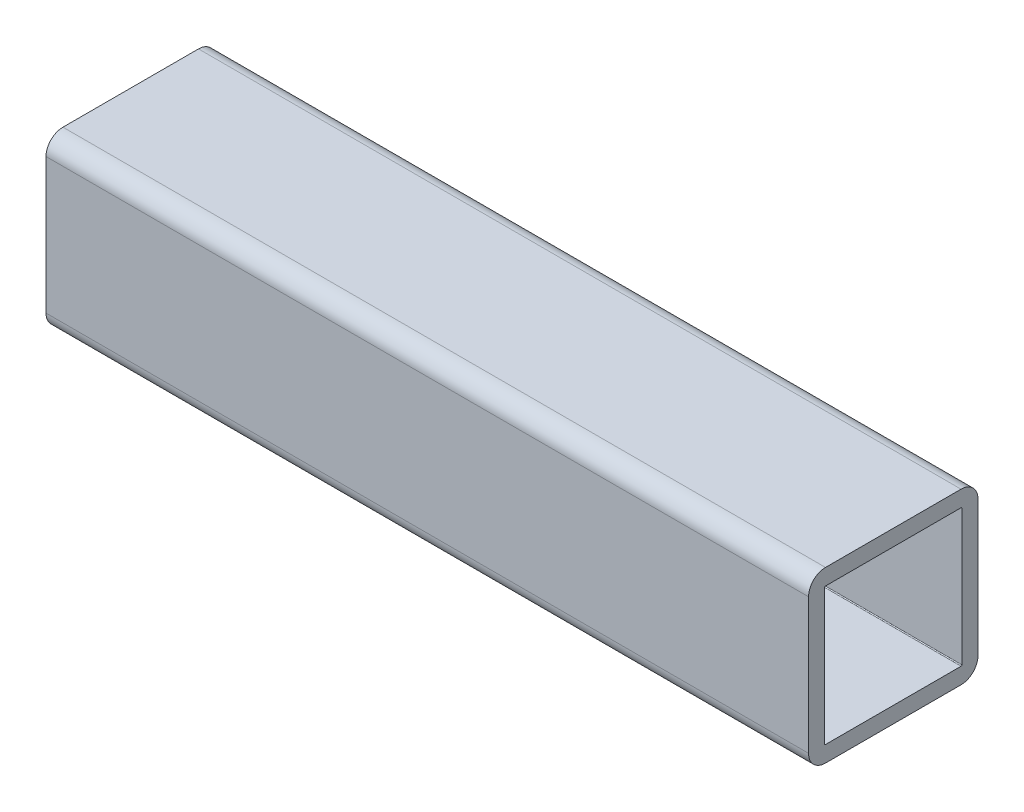
SolidWorks part; units mm, degrees
ref_plane "Front Plane" through (0, 0, 0) normal (0, 0, 1) x (1, 0, 0)
ref_plane "Top Plane" through (0, 0, 0) normal (0, 1, 0) x (1, 0, 0)
ref_plane "Right Plane" through (0, 0, 0) normal (1, 0, 0) x (0, 0, -1)
sketch "Sketch1" plane through (0, 0, 0) normal (0, 0, 1) x (1, 0, 0)
  line L0 (0, 0) -> (114.3, 0)
  dimension "D1" = 114.3
other "Square tube - configured 2 X 2 X 0.25(1)"
ref_plane "Plane1" through (0, 0, 0) normal (1, 0, 0) x (0, 1, 0)
sketch "Sketch11" plane through (0, 0, 0) normal (1, 0, 0) x (0, 1, 0)
  line L0 (-10.16, -10.287) -> (10.16, -10.287)
  line L1 (-10.287, -10.16) -> (-10.287, 10.16)
  line L2 (10.16, 10.287) -> (-10.16, 10.287)
  line L3 (10.287, 10.16) -> (10.287, -10.16)
  line L4 (-10.16, -12.7) -> (10.16, -12.7)
  line L5 (-12.7, -10.16) -> (-12.7, 10.16)
  line L6 (10.16, 12.7) -> (-10.16, 12.7)
  line L7 (12.7, 10.16) -> (12.7, -10.16)
  line L8 (0, 0) -> (10.287, 0) construction
  line L9 (0, 0) -> (0, 10.287) construction
  arc A0 (12.7, 10.16) -> (10.16, 12.7) centre (10.16, 10.16) ccw
  arc A1 (10.16, -12.7) -> (12.7, -10.16) centre (10.16, -10.16) ccw
  arc A2 (-12.7, -10.16) -> (-10.16, -12.7) centre (-10.16, -10.16) ccw
  arc A3 (-10.16, 12.7) -> (-12.7, 10.16) centre (-10.16, 10.16) ccw
  arc A4 (-10.16, 10.287) -> (-10.287, 10.16) centre (-10.16, 10.16) ccw
  arc A5 (10.287, 10.16) -> (10.16, 10.287) centre (10.16, 10.16) ccw
  arc A6 (10.16, -10.287) -> (10.287, -10.16) centre (10.16, -10.16) ccw
  arc A7 (-10.287, -10.16) -> (-10.16, -10.287) centre (-10.16, -10.16) ccw
  point P3 (0, 12.7)
  point P4 (12.7, 0)
  point P5 (0, -12.7)
  point P6 (-12.7, 0)
  point P7 (-12.7, 12.7)
  point P8 (-12.7, -12.7)
  point P33 (0, 0)
  point P35 (12.7, -12.7)
  point P36 (12.7, 12.7)
  point P37 (0, 0)
  dimension "D1" = 2.54
  dimension "Thickness" = 2.413
  dimension "V_leg" = 25.4
